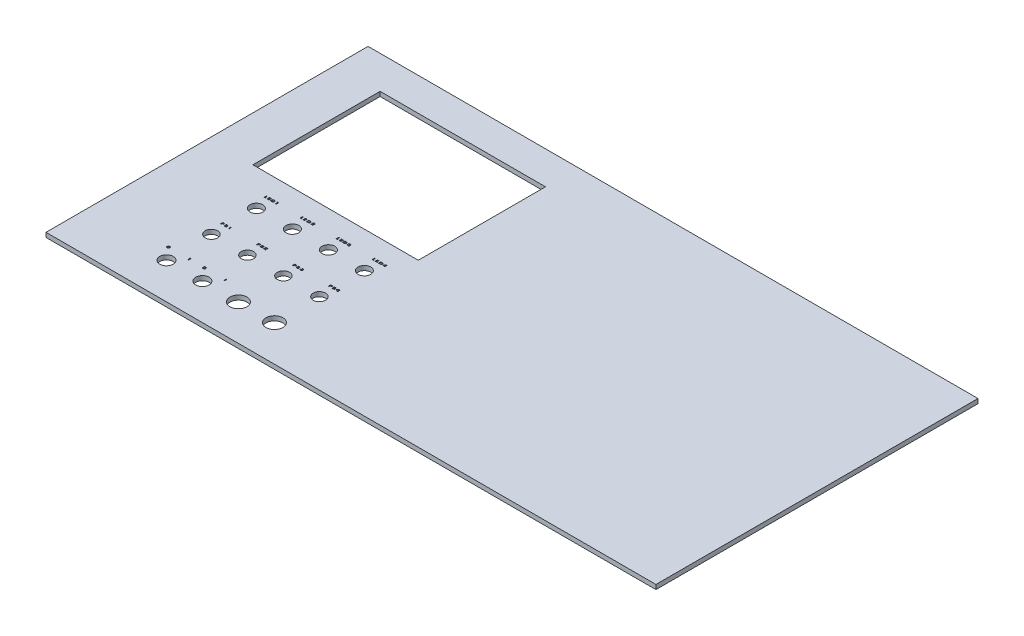
SolidWorks part; units mm, degrees
ref_plane "Front Plane" through (0, 0, 0) normal (0, 0, 1) x (1, 0, 0)
ref_plane "Top Plane" through (0, 0, 0) normal (0, 1, 0) x (1, 0, 0)
ref_plane "Right Plane" through (0, 0, 0) normal (1, 0, 0) x (0, 0, -1)
sketch "Sketch1" plane through (0, 0, 0) normal (0, 1, 0) x (1, 0, 0)
  line L1 (0, 0) -> (861.06, 0)
  line L2 (0, 0) -> (0, 454.66)
  line L3 (0, 454.66) -> (861.06, 454.66)
  line L4 (861.06, 0) -> (861.06, 454.66)
  dimension "D1" = 861.06
  dimension "D2" = 454.66
extrude "Boss-Extrude1" add sketch "Sketch1" along normal blind 6.35
sketch "Sketch3" plane through (0, 6.35, 0) normal (0, 1, 0) x (1, 0, 0)
  line L0 (0, 0) -> (861.06, 0) construction
  line L1 (63.5, 408.178) -> (296.926, 408.178)
  line L2 (63.5, 408.178) -> (63.5, 228.6)
  line L3 (63.5, 228.6) -> (296.926, 228.6)
  line L4 (296.926, 408.178) -> (296.926, 228.6)
  line L5 (0, 454.66) -> (0, 0) construction
  point P4 (180.213, 228.6)
  point P7 (63.5, 318.389)
  dimension "D1" = 233.426
  dimension "D2" = 179.578
  dimension "D3" = 228.6
  dimension "D4" = 63.5
extrude "Cut-Extrude2" cut sketch "Sketch3" against normal through all
sketch "Sketch4" plane through (0, 6.35, 0) normal (0, 1, 0) x (1, 0, 0)
  line L2 (63.5, 228.6) -> (296.926, 228.6) construction
  line L4 (170.053, 177.8) -> (220.853, 177.8) construction
  circle A0 centre (119.253, 177.8) radius 9.017
  circle A1 centre (170.053, 177.8) radius 9.017
  circle A2 centre (220.853, 177.8) radius 9.017
  circle A3 centre (271.653, 177.8) radius 9.017
  point P3 (212.6408, 190.5)
  point P11 (195.453, 177.8)
  point P12 (180.213, 228.6)
  dimension "D1" = 18.034
  dimension "D3" = 50.8
  dimension "D4" = 15.24
  dimension "D5" = 50.8
  dimension "D2" = 4
extrude "Cut-Extrude3" cut sketch "Sketch4" against normal through all
sketch "Sketch5" plane through (0, 6.35, 0) normal (0, 1, 0) x (1, 0, 0)
  circle A0 centre (119.253, 114.3) radius 8.763
  circle A1 centre (170.053, 114.3) radius 8.763
  circle A2 centre (220.853, 114.3) radius 8.763
  circle A3 centre (271.653, 114.3) radius 8.763
  circle A4 centre (119.253, 177.8) radius 9.017 construction
  point P2 (202.8159, 140.8339)
  point P3 (0, 0)
  point P10 (0, 0)
  dimension "D1" = 17.526
  dimension "D3" = 63.5
  dimension "D2" = 4
extrude "Cut-Extrude4" cut sketch "Sketch5" against normal through all
sketch "Sketch6" plane through (0, 6.35, 0) normal (0, 1, 0) x (1, 0, 0)
  circle A0 centre (119.253, 50.8) radius 9.525
  circle A1 centre (170.053, 50.8) radius 9.525
  circle A4 centre (271.653, 50.8) radius 9.525 [skipped]
  circle A5 centre (220.853, 50.8) radius 9.525 [skipped]
  point P2 (106.6111, 82.5815)
  point P3 (0, 0)
  dimension "D1" = 19.05
  dimension "D3" = 63.5
  dimension "D2" = 4
extrude "Cut-Extrude5" cut sketch "Sketch6" against normal through all
sketch "Sketch7" plane through (0, 6.35, 0) normal (0, 1, 0) x (1, 0, 0)
  circle A0 centre (220.853, 50.8) radius 11.938
  circle A1 centre (271.653, 50.8) radius 11.938
  circle A4 centre (373.253, 50.8) radius 11.938 [skipped]
  circle A5 centre (322.453, 50.8) radius 11.938 [skipped]
  point P2 (518.8063, 238.76)
  point P5 (461.9947, 240.5423)
  point P6 (206.3464, 86.112)
  point P7 (0, 0)
  dimension "D3" = 23.876
  dimension "D1" = 4
extrude "Cut-Extrude6" cut sketch "Sketch7" against normal through all
sketch "Sketch8" plane through (0, 6.35, 0) normal (0, 1, 0) x (1, 0, 0)
  line L0 (0, 454.66) -> (0, 0) construction
  circle A0 centre (119.253, 177.8) radius 9.017 construction
  circle A1 centre (119.253, 114.3) radius 8.763 construction
  arc A2 (106.553, 66.6623) -> (131.953, 66.6623) centre (119.253, 50.8) cw construction
  arc A3 (157.353, 66.6623) -> (182.753, 66.6623) centre (170.053, 50.8) cw construction
  text T0 "LED1\r\n" font "Century Gothic" height 3.5
  text T1 "LED2" font "Century Gothic" height 3.5
  text T2 "PB1" font "Century Gothic" height 3.5
  text T3 "LED3" font "Century Gothic" height 3.5
  text T4 "LED4" font "Century Gothic" height 3.5
  text T5 "PB2" font "Century Gothic" height 3.5
  text T6 "PB3" font "Century Gothic" height 3.5
  text T7 "PB4" font "Century Gothic" height 3.5
  text T8 "0" font "Century Gothic" height 3.5
  text T9 "1" font "Century Gothic" height 3.5
  text T10 "0" font "Century Gothic" height 3.5
  text T11 "1" font "Century Gothic" height 3.5
  point P20 (119.253, 71.12)
  point P69 (0, 0)
  point P70 (217.5321, 77.0983)
  point P71 (0, 0)
  point P72 (0, 0)
  point P73 (205.7539, 73.5146)
  point P74 (0, 0)
  point P75 (197.1299, 65.2642)
  point P76 (196.1837, 65.2642)
  point P77 (0, 0)
  point P78 (0, 0)
  point P79 (0, 0)
  point P80 (194.5008, 65.2642)
  point P93 (0, 0)
  dimension "D11" = 20.32
  dimension "D1" = 110.49
  dimension "D2" = 19.05
  dimension "D3" = 50.8
  dimension "D4" = 101.6
  dimension "D5" = 152.4
  dimension "D6" = 112.268
  dimension "D7" = 19.05
  dimension "D8" = 50.8041
  dimension "D9" = 101.6
  dimension "D10" = 152.4
  dimension "D12" = 25.4
  dimension "D13" = 2
extrude "Cut-Extrude7" cut sketch "Sketch8" against normal blind 1.27
